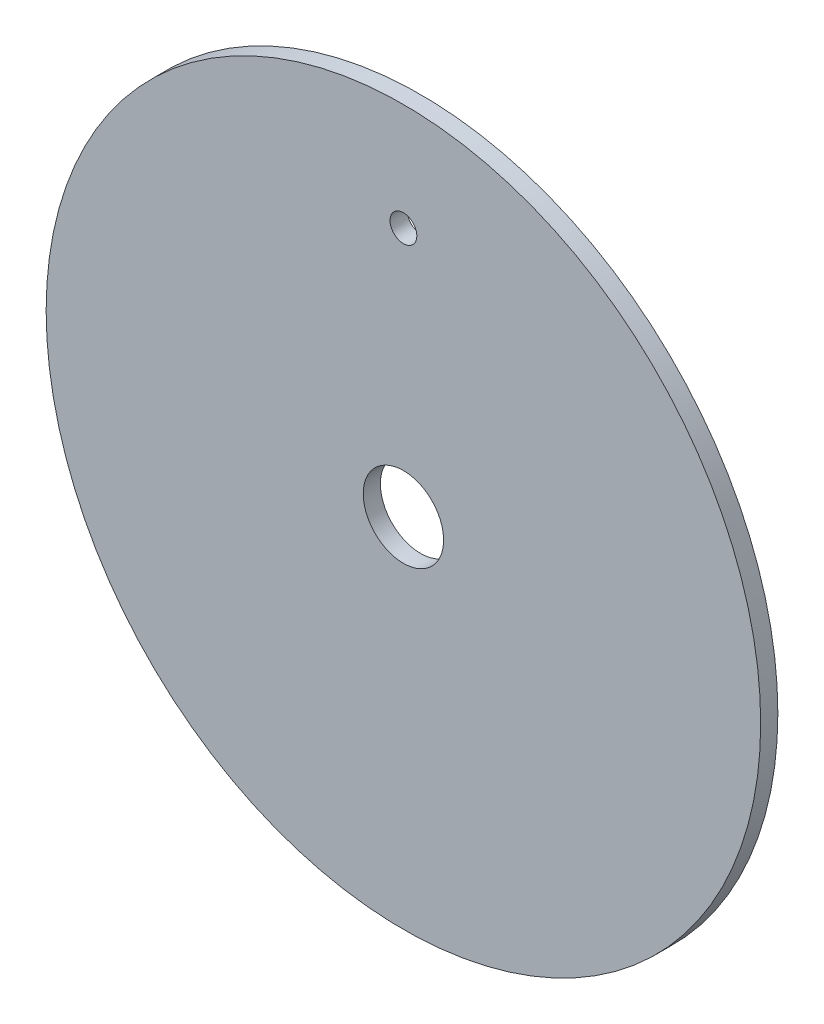
SolidWorks part; units mm, degrees
material "Plain Carbon Steel"
ref_plane "Front Plane" through (0, 0, 0) normal (0, 0, 1) x (1, 0, 0)
ref_plane "Top Plane" through (0, 0, 0) normal (0, 1, 0) x (1, 0, 0)
ref_plane "Right Plane" through (0, 0, 0) normal (1, 0, 0) x (0, 0, -1)
sketch "Sketch1" plane through (0, 0, 0) normal (0, 0, 1) x (1, 0, 0)
  circle A0 centre (0, 0) radius 63.5
  circle A1 centre (0, 0) radius 7.1438
  dimension "D1" = 127
  dimension "D2" = 14.2875
extrude "Boss-Extrude1" add sketch "Sketch1" along normal blind 3.048
sketch "Sketch2" plane through (0, 0, 3.048) normal (0, 0, 1) x (1, 0, 0)
  circle A0 centre (0, 0) radius 38.1 construction
  circle A1 centre (0, 44.45) radius 2.3812
  point P5 (26.6043, 34.8712)
  point P6 (1.213, 45.1822)
  dimension "D1" = 76.2
  dimension "D2" = 4.7625
  dimension "D3" = 44.45
extrude "Cut-Extrude1" cut sketch "Sketch2" against normal through all contours A1
